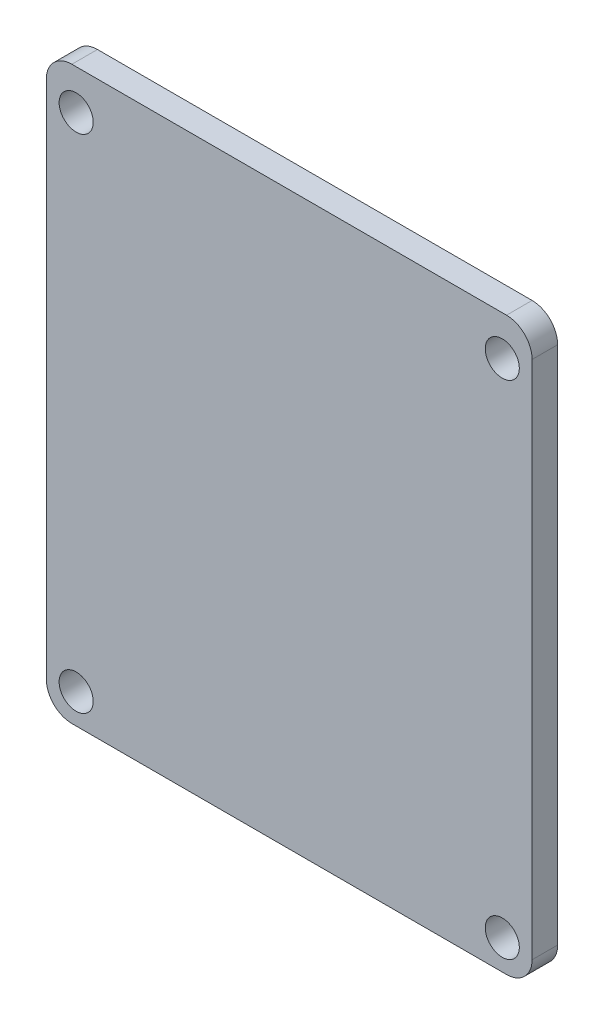
SolidWorks part; units mm, degrees
ref_plane "Přední rovina" through (0, 0, 0) normal (0, 0, 1) x (1, 0, 0)
ref_plane "Horní rovina" through (0, 0, 0) normal (0, 1, 0) x (1, 0, 0)
ref_plane "Pravá rovina" through (0, 0, 0) normal (1, 0, 0) x (0, 0, -1)
sketch "Skica1" plane through (0, 0, 0) normal (0, 0, 1) x (1, 0, 0)
  line L1 (0, 0) -> (57, 0)
  line L2 (0, 0) -> (0, 67)
  line L3 (0, 67) -> (57, 67)
  line L4 (57, 0) -> (57, 67)
  circle A0 centre (3.5, 62.3502) radius 2
  circle A1 centre (53.5, 62.3502) radius 2
  circle A2 centre (53.5, 3.5) radius 2
  circle A3 centre (3.5, 3.5) radius 2
  dimension "D5" = 4
  dimension "D1" = 67
  dimension "D2" = 57
  dimension "D3" = 3.5
  dimension "D4" = 3.5
  dimension "D6" = 50
  dimension "D7" = 58.8502
  dimension "D8" = 3.5
  dimension "D9" = 3.5
  dimension "D10" = 4.6498
extrude "Přidat vysunutím1" add sketch "Skica1" along normal blind 3
sketch "Skica2" plane through (0, 0, 0) normal (0, 0, -1) x (-1, 0, 0)
  text T0 "<r90>P</r>" font "Century Gothic" height 20
extrude "Přidat vysunutím2" add sketch "Skica2" along normal blind 1
fillet "Zaoblit1" radius 3 4 edges at (57, 67, 1.5) (0, 67, 1.5) (0, 0, 1.5) (57, 0, 1.5)
